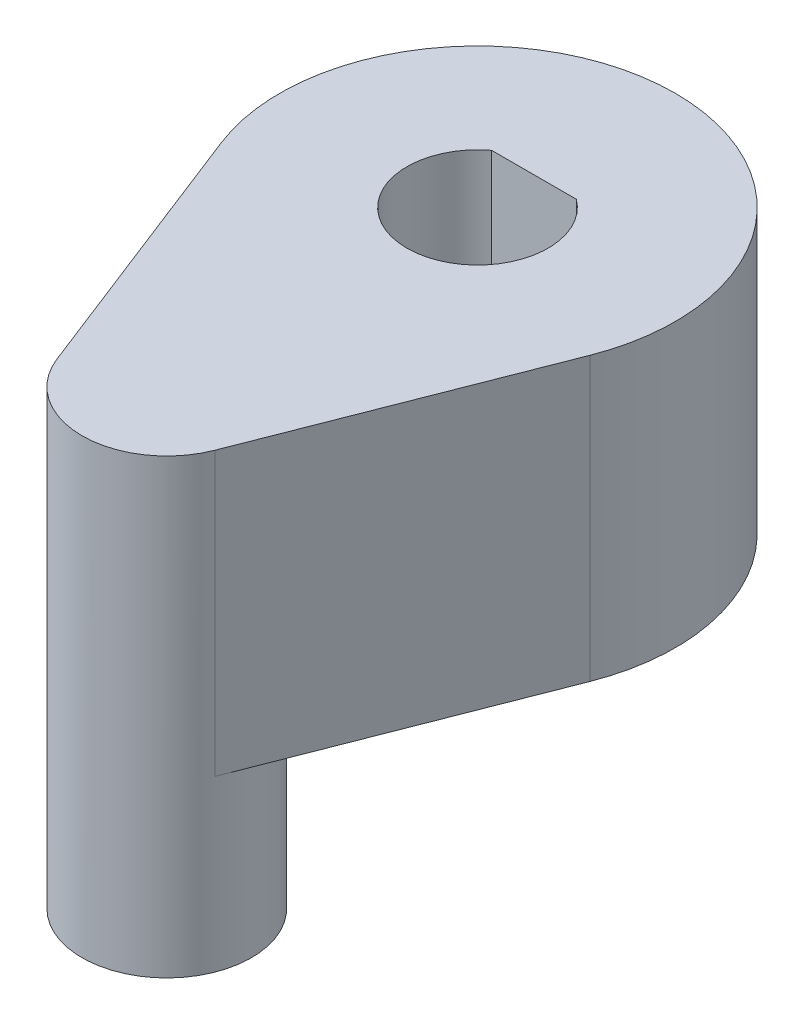
SolidWorks part; units mm, degrees
ref_plane "Front" through (0, 0, 0) normal (0, 0, 1) x (1, 0, 0)
ref_plane "Top" through (0, 0, 0) normal (0, 1, 0) x (1, 0, 0)
ref_plane "Right" through (0, 0, 0) normal (1, 0, 0) x (0, 0, -1)
sketch "Sketch1" plane through (0, 0, 0) normal (0, 1, 0) x (1, 0, 0)
  line L0 (-1.5, 2) -> (1.5, 2)
  arc A0 (-1.5, 2) -> (1.5, 2) centre (0, 0) ccw
  circle A1 centre (0, 0) radius 7
  dimension "D1" = 5
  dimension "D3" = 14
  dimension "D2" = 2
extrude "Boss-Extrude1" add sketch "Sketch1" along normal blind 10
sketch "Sketch3" plane through (0, 0, 0) normal (0, 1, 0) x (1, 0, 0)
  line L1 (-2.85, 5.25) -> (2.85, 5.25)
  line L2 (-2.85, 5.25) -> (-2.85, 2.75)
  line L3 (-2.85, 2.75) -> (2.85, 2.75)
  line L4 (2.85, 5.25) -> (2.85, 2.75)
  line L5 (-2.85, 5.25) -> (2.85, 2.75) construction
  line L6 (-2.85, 2.75) -> (2.85, 5.25) construction
  point P0 (0, 4)
  dimension "D1" = 2.5
  dimension "D2" = 5.7
  dimension "D3" = 4
extrude "Cut-Extrude1" cut sketch "Sketch3" along normal blind 8
sketch "Sketch6" plane through (0, 0, 0) normal (0, 0, 1) x (1, 0, 0)
  circle A0 centre (0, 5) radius 1.55
  dimension "D1" = 3.1
  dimension "D2" = 5
extrude "Cut-Extrude2" cut sketch "Sketch6" against normal through all
sketch "Sketch7" plane through (0, 0, 0) normal (0, -1, 0) x (1, 0, 0)
  circle A0 centre (0, 11) radius 3
  dimension "D1" = 6
  dimension "D2" = 11
extrude "Boss-Extrude2" add sketch "Sketch7" along normal blind 6 and the other way up to surface (10 mm away) other way up to face at (0, 10, 7)
sketch "Sketch9" plane through (0, 10, 0) normal (0, 1, 0) x (1, 0, 0)
  line L0 (-6.5208, -2.5455) -> (-2.7946, -12.0909)
  line L1 (2.7946, -12.0909) -> (6.5208, -2.5455)
  circle A0 centre (0, 0) radius 7 construction
  circle A1 centre (0, -11) radius 3
  circle A2 centre (0, -11) radius 3
  circle A3 centre (0, 0) radius 7
  circle M5 centre (0, -11) radius 3
  dimension "D1" = 0
extrude "Boss-Extrude3" add sketch "Sketch9" against normal up to surface (10 mm away) contours A3 L0 L1 M5 up to face at (0, 0, 0.25)
